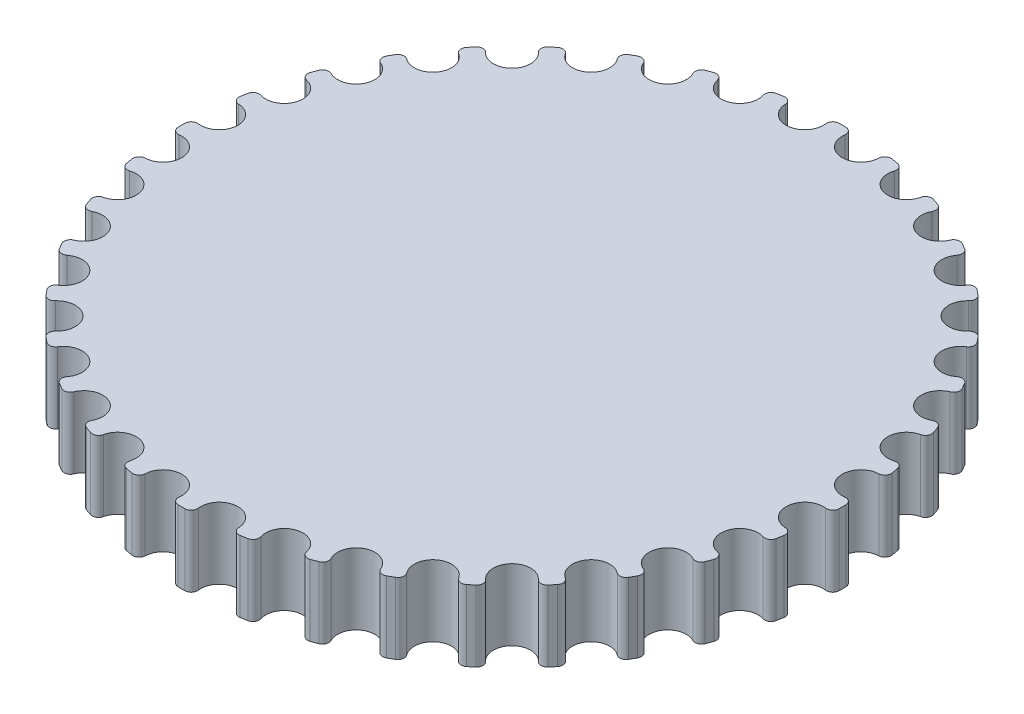
SolidWorks part; units mm, degrees
ref_plane "Front Plane" through (0, 0, 0) normal (0, 0, 1) x (1, 0, 0)
ref_plane "Top Plane" through (0, 0, 0) normal (0, 1, 0) x (1, 0, 0)
ref_plane "Right Plane" through (0, 0, 0) normal (1, 0, 0) x (0, 0, -1)
sketch "Sketch1" plane through (0, 0, 0) normal (0, 1, 0) x (1, 0, 0)
  line L0 (0, 0) -> (27.8866, 0) construction
  line L1 (0, 0) -> (27.7805, 2.4305) construction
  circle A0 centre (0, 0) radius 27.8866 construction
  arc A1 (27.0068, 3.9419) -> (27.281, 0.8076) centre (27.072, 2.3685) ccw
  arc A2 (27.281, 0.8076) -> (27.8852, 0.2844) centre (27.3518, 0.2789) cw
  arc A3 (27.8852, 0.2844) -> (27.8866, 0) centre (0, 0) cw
  arc A4 (27.0068, 3.9419) -> (27.5109, 4.5621) centre (26.9847, 4.4749) ccw
  arc A5 (27.5109, 4.5621) -> (27.463, 4.8425) centre (0, 0) ccw
  arc A6 (27.5109, -4.5621) -> (27.463, -4.8425) centre (0, 0) cw
  arc A7 (27.0068, -3.9419) -> (27.5109, -4.5621) centre (26.9847, -4.4749) cw
  arc A8 (27.281, -0.8076) -> (27.0068, -3.9419) centre (27.072, -2.3685) ccw
  arc A9 (27.281, -0.8076) -> (27.8852, -0.2844) centre (27.3518, -0.2789) ccw
  arc A10 (27.8852, -0.2844) -> (27.8866, 0) centre (0, 0) ccw
  arc A11 (26.3008, -9.2701) -> (26.2049, -9.5378) centre (0, 0) cw
  arc A12 (25.912, -8.5717) -> (26.3008, -9.2701) centre (25.7977, -9.0928) cw
  arc A13 (26.7263, -5.5327) -> (25.912, -8.5717) centre (26.2495, -7.0335) ccw
  arc A14 (26.7263, -5.5327) -> (27.4122, -5.1223) centre (26.8878, -5.0243) ccw
  arc A15 (27.4122, -5.1223) -> (27.463, -4.8425) centre (0, 0) ccw
  arc A16 (24.2915, -13.6963) -> (24.1505, -13.9433) centre (0, 0) cw
  arc A17 (24.0299, -12.9411) -> (24.2915, -13.6963) centre (23.8268, -13.4343) cw
  arc A18 (25.3596, -10.0896) -> (24.0299, -12.9411) centre (24.6293, -11.4848) ccw
  arc A19 (25.3596, -10.0896) -> (26.1062, -9.8045) centre (25.6069, -9.617) ccw
  arc A20 (26.1062, -9.8045) -> (26.2049, -9.5378) centre (0, 0) ccw
  arc A21 (21.5441, -17.7064) -> (21.3624, -17.9252) centre (0, 0) cw
  arc A22 (21.4176, -16.9172) -> (21.5441, -17.7064) centre (21.132, -17.3677) cw
  arc A23 (23.2222, -14.3399) -> (21.4176, -16.9172) centre (22.2608, -15.5872) ccw
  arc A24 (23.2222, -14.3399) -> (24.0071, -14.1889) centre (23.5479, -13.9175) ccw
  arc A25 (24.0071, -14.1889) -> (24.1505, -13.9433) centre (0, 0) ccw
  arc A26 (18.1421, -21.1785) -> (17.9252, -21.3624) centre (0, 0) cw
  arc A27 (18.1546, -20.3793) -> (18.1421, -21.1785) centre (17.7951, -20.7734) cw
  arc A28 (20.3793, -18.1546) -> (18.1546, -20.3793) centre (19.2159, -19.2159) ccw
  arc A29 (20.3793, -18.1546) -> (21.1785, -18.1421) centre (20.7734, -17.7951) ccw
  arc A30 (21.1785, -18.1421) -> (21.3624, -17.9252) centre (0, 0) ccw
  arc A31 (14.1889, -24.0071) -> (13.9433, -24.1505) centre (0, 0) cw
  arc A32 (14.3399, -23.2222) -> (14.1889, -24.0071) centre (13.9175, -23.5479) cw
  arc A33 (16.9172, -21.4176) -> (14.3399, -23.2222) centre (15.5872, -22.2608) ccw
  arc A34 (16.9172, -21.4176) -> (17.7064, -21.5441) centre (17.3677, -21.132) ccw
  arc A35 (17.7064, -21.5441) -> (17.9252, -21.3624) centre (0, 0) ccw
  arc A36 (9.8045, -26.1062) -> (9.5378, -26.2049) centre (0, 0) cw
  arc A37 (10.0896, -25.3596) -> (9.8045, -26.1062) centre (9.617, -25.6069) cw
  arc A38 (12.9411, -24.0299) -> (10.0896, -25.3596) centre (11.4848, -24.6293) ccw
  arc A39 (12.9411, -24.0299) -> (13.6963, -24.2915) centre (13.4343, -23.8268) ccw
  arc A40 (13.6963, -24.2915) -> (13.9433, -24.1505) centre (0, 0) ccw
  arc A41 (5.1223, -27.4122) -> (4.8425, -27.463) centre (0, 0) cw
  arc A42 (5.5327, -26.7263) -> (5.1223, -27.4122) centre (5.0243, -26.8878) cw
  arc A43 (8.5717, -25.912) -> (5.5327, -26.7263) centre (7.0335, -26.2495) ccw
  arc A44 (8.5717, -25.912) -> (9.2701, -26.3008) centre (9.0928, -25.7977) ccw
  arc A45 (9.2701, -26.3008) -> (9.5378, -26.2049) centre (0, 0) ccw
  arc A46 (0.2844, -27.8852) -> (0, -27.8866) centre (0, 0) cw
  arc A47 (0.8076, -27.281) -> (0.2844, -27.8852) centre (0.2789, -27.3518) cw
  arc A48 (3.9419, -27.0068) -> (0.8076, -27.281) centre (2.3685, -27.072) ccw
  arc A49 (3.9419, -27.0068) -> (4.5621, -27.5109) centre (4.4749, -26.9847) ccw
  arc A50 (4.5621, -27.5109) -> (4.8425, -27.463) centre (0, 0) ccw
  arc A51 (-4.5621, -27.5109) -> (-4.8425, -27.463) centre (0, 0) cw
  arc A52 (-3.9419, -27.0068) -> (-4.5621, -27.5109) centre (-4.4749, -26.9847) cw
  arc A53 (-0.8076, -27.281) -> (-3.9419, -27.0068) centre (-2.3685, -27.072) ccw
  arc A54 (-0.8076, -27.281) -> (-0.2844, -27.8852) centre (-0.2789, -27.3518) ccw
  arc A55 (-0.2844, -27.8852) -> (0, -27.8866) centre (0, 0) ccw
  arc A56 (-9.2701, -26.3008) -> (-9.5378, -26.2049) centre (0, 0) cw
  arc A57 (-8.5717, -25.912) -> (-9.2701, -26.3008) centre (-9.0928, -25.7977) cw
  arc A58 (-5.5327, -26.7263) -> (-8.5717, -25.912) centre (-7.0335, -26.2495) ccw
  arc A59 (-5.5327, -26.7263) -> (-5.1223, -27.4122) centre (-5.0243, -26.8878) ccw
  arc A60 (-5.1223, -27.4122) -> (-4.8425, -27.463) centre (0, 0) ccw
  arc A61 (-13.6963, -24.2915) -> (-13.9433, -24.1505) centre (0, 0) cw
  arc A62 (-12.9411, -24.0299) -> (-13.6963, -24.2915) centre (-13.4343, -23.8268) cw
  arc A63 (-10.0896, -25.3596) -> (-12.9411, -24.0299) centre (-11.4848, -24.6293) ccw
  arc A64 (-10.0896, -25.3596) -> (-9.8045, -26.1062) centre (-9.617, -25.6069) ccw
  arc A65 (-9.8045, -26.1062) -> (-9.5378, -26.2049) centre (0, 0) ccw
  arc A66 (-17.7064, -21.5441) -> (-17.9252, -21.3624) centre (0, 0) cw
  arc A67 (-16.9172, -21.4176) -> (-17.7064, -21.5441) centre (-17.3677, -21.132) cw
  arc A68 (-14.3399, -23.2222) -> (-16.9172, -21.4176) centre (-15.5872, -22.2608) ccw
  arc A69 (-14.3399, -23.2222) -> (-14.1889, -24.0071) centre (-13.9175, -23.5479) ccw
  arc A70 (-14.1889, -24.0071) -> (-13.9433, -24.1505) centre (0, 0) ccw
  arc A71 (-21.1785, -18.1421) -> (-21.3624, -17.9252) centre (0, 0) cw
  arc A72 (-20.3793, -18.1546) -> (-21.1785, -18.1421) centre (-20.7734, -17.7951) cw
  arc A73 (-18.1546, -20.3793) -> (-20.3793, -18.1546) centre (-19.2159, -19.2159) ccw
  arc A74 (-18.1546, -20.3793) -> (-18.1421, -21.1785) centre (-17.7951, -20.7734) ccw
  arc A75 (-18.1421, -21.1785) -> (-17.9252, -21.3624) centre (0, 0) ccw
  arc A76 (-24.0071, -14.1889) -> (-24.1505, -13.9433) centre (0, 0) cw
  arc A77 (-23.2222, -14.3399) -> (-24.0071, -14.1889) centre (-23.5479, -13.9175) cw
  arc A78 (-21.4176, -16.9172) -> (-23.2222, -14.3399) centre (-22.2608, -15.5872) ccw
  arc A79 (-21.4176, -16.9172) -> (-21.5441, -17.7064) centre (-21.132, -17.3677) ccw
  arc A80 (-21.5441, -17.7064) -> (-21.3624, -17.9252) centre (0, 0) ccw
  arc A81 (-26.1062, -9.8045) -> (-26.2049, -9.5378) centre (0, 0) cw
  arc A82 (-25.3596, -10.0896) -> (-26.1062, -9.8045) centre (-25.6069, -9.617) cw
  arc A83 (-24.0299, -12.9411) -> (-25.3596, -10.0896) centre (-24.6293, -11.4848) ccw
  arc A84 (-24.0299, -12.9411) -> (-24.2915, -13.6963) centre (-23.8268, -13.4343) ccw
  arc A85 (-24.2915, -13.6963) -> (-24.1505, -13.9433) centre (0, 0) ccw
  arc A86 (-27.4122, -5.1223) -> (-27.463, -4.8425) centre (0, 0) cw
  arc A87 (-26.7263, -5.5327) -> (-27.4122, -5.1223) centre (-26.8878, -5.0243) cw
  arc A88 (-25.912, -8.5717) -> (-26.7263, -5.5327) centre (-26.2495, -7.0335) ccw
  arc A89 (-25.912, -8.5717) -> (-26.3008, -9.2701) centre (-25.7977, -9.0928) ccw
  arc A90 (-26.3008, -9.2701) -> (-26.2049, -9.5378) centre (0, 0) ccw
  arc A91 (-27.8852, -0.2844) -> (-27.8866, 0) centre (0, 0) cw
  arc A92 (-27.281, -0.8076) -> (-27.8852, -0.2844) centre (-27.3518, -0.2789) cw
  arc A93 (-27.0068, -3.9419) -> (-27.281, -0.8076) centre (-27.072, -2.3685) ccw
  arc A94 (-27.0068, -3.9419) -> (-27.5109, -4.5621) centre (-26.9847, -4.4749) ccw
  arc A95 (-27.5109, -4.5621) -> (-27.463, -4.8425) centre (0, 0) ccw
  arc A96 (-27.5109, 4.5621) -> (-27.463, 4.8425) centre (0, 0) cw
  arc A97 (-27.0068, 3.9419) -> (-27.5109, 4.5621) centre (-26.9847, 4.4749) cw
  arc A98 (-27.281, 0.8076) -> (-27.0068, 3.9419) centre (-27.072, 2.3685) ccw
  arc A99 (-27.281, 0.8076) -> (-27.8852, 0.2844) centre (-27.3518, 0.2789) ccw
  arc A100 (-27.8852, 0.2844) -> (-27.8866, 0) centre (0, 0) ccw
  arc A101 (-26.3008, 9.2701) -> (-26.2049, 9.5378) centre (0, 0) cw
  arc A102 (-25.912, 8.5717) -> (-26.3008, 9.2701) centre (-25.7977, 9.0928) cw
  arc A103 (-26.7263, 5.5327) -> (-25.912, 8.5717) centre (-26.2495, 7.0335) ccw
  arc A104 (-26.7263, 5.5327) -> (-27.4122, 5.1223) centre (-26.8878, 5.0243) ccw
  arc A105 (-27.4122, 5.1223) -> (-27.463, 4.8425) centre (0, 0) ccw
  arc A106 (-24.2915, 13.6963) -> (-24.1505, 13.9433) centre (0, 0) cw
  arc A107 (-24.0299, 12.9411) -> (-24.2915, 13.6963) centre (-23.8268, 13.4343) cw
  arc A108 (-25.3596, 10.0896) -> (-24.0299, 12.9411) centre (-24.6293, 11.4848) ccw
  arc A109 (-25.3596, 10.0896) -> (-26.1062, 9.8045) centre (-25.6069, 9.617) ccw
  arc A110 (-26.1062, 9.8045) -> (-26.2049, 9.5378) centre (0, 0) ccw
  arc A111 (-21.5441, 17.7064) -> (-21.3624, 17.9252) centre (0, 0) cw
  arc A112 (-21.4176, 16.9172) -> (-21.5441, 17.7064) centre (-21.132, 17.3677) cw
  arc A113 (-23.2222, 14.3399) -> (-21.4176, 16.9172) centre (-22.2608, 15.5872) ccw
  arc A114 (-23.2222, 14.3399) -> (-24.0071, 14.1889) centre (-23.5479, 13.9175) ccw
  arc A115 (-24.0071, 14.1889) -> (-24.1505, 13.9433) centre (0, 0) ccw
  arc A116 (-18.1421, 21.1785) -> (-17.9252, 21.3624) centre (0, 0) cw
  arc A117 (-18.1546, 20.3793) -> (-18.1421, 21.1785) centre (-17.7951, 20.7734) cw
  arc A118 (-20.3793, 18.1546) -> (-18.1546, 20.3793) centre (-19.2159, 19.2159) ccw
  arc A119 (-20.3793, 18.1546) -> (-21.1785, 18.1421) centre (-20.7734, 17.7951) ccw
  arc A120 (-21.1785, 18.1421) -> (-21.3624, 17.9252) centre (0, 0) ccw
  arc A121 (-14.1889, 24.0071) -> (-13.9433, 24.1505) centre (0, 0) cw
  arc A122 (-14.3399, 23.2222) -> (-14.1889, 24.0071) centre (-13.9175, 23.5479) cw
  arc A123 (-16.9172, 21.4176) -> (-14.3399, 23.2222) centre (-15.5872, 22.2608) ccw
  arc A124 (-16.9172, 21.4176) -> (-17.7064, 21.5441) centre (-17.3677, 21.132) ccw
  arc A125 (-17.7064, 21.5441) -> (-17.9252, 21.3624) centre (0, 0) ccw
  arc A126 (-9.8045, 26.1062) -> (-9.5378, 26.2049) centre (0, 0) cw
  arc A127 (-10.0896, 25.3596) -> (-9.8045, 26.1062) centre (-9.617, 25.6069) cw
  arc A128 (-12.9411, 24.0299) -> (-10.0896, 25.3596) centre (-11.4848, 24.6293) ccw
  arc A129 (-12.9411, 24.0299) -> (-13.6963, 24.2915) centre (-13.4343, 23.8268) ccw
  arc A130 (-13.6963, 24.2915) -> (-13.9433, 24.1505) centre (0, 0) ccw
  arc A131 (-5.1223, 27.4122) -> (-4.8425, 27.463) centre (0, 0) cw
  arc A132 (-5.5327, 26.7263) -> (-5.1223, 27.4122) centre (-5.0243, 26.8878) cw
  arc A133 (-8.5717, 25.912) -> (-5.5327, 26.7263) centre (-7.0335, 26.2495) ccw
  arc A134 (-8.5717, 25.912) -> (-9.2701, 26.3008) centre (-9.0928, 25.7977) ccw
  arc A135 (-9.2701, 26.3008) -> (-9.5378, 26.2049) centre (0, 0) ccw
  arc A136 (-0.2844, 27.8852) -> (0, 27.8866) centre (0, 0) cw
  arc A137 (-0.8076, 27.281) -> (-0.2844, 27.8852) centre (-0.2789, 27.3518) cw
  arc A138 (-3.9419, 27.0068) -> (-0.8076, 27.281) centre (-2.3685, 27.072) ccw
  arc A139 (-3.9419, 27.0068) -> (-4.5621, 27.5109) centre (-4.4749, 26.9847) ccw
  arc A140 (-4.5621, 27.5109) -> (-4.8425, 27.463) centre (0, 0) ccw
  arc A141 (4.5621, 27.5109) -> (4.8425, 27.463) centre (0, 0) cw
  arc A142 (3.9419, 27.0068) -> (4.5621, 27.5109) centre (4.4749, 26.9847) cw
  arc A143 (0.8076, 27.281) -> (3.9419, 27.0068) centre (2.3685, 27.072) ccw
  arc A144 (0.8076, 27.281) -> (0.2844, 27.8852) centre (0.2789, 27.3518) ccw
  arc A145 (0.2844, 27.8852) -> (0, 27.8866) centre (0, 0) ccw
  arc A146 (9.2701, 26.3008) -> (9.5378, 26.2049) centre (0, 0) cw
  arc A147 (8.5717, 25.912) -> (9.2701, 26.3008) centre (9.0928, 25.7977) cw
  arc A148 (5.5327, 26.7263) -> (8.5717, 25.912) centre (7.0335, 26.2495) ccw
  arc A149 (5.5327, 26.7263) -> (5.1223, 27.4122) centre (5.0243, 26.8878) ccw
  arc A150 (5.1223, 27.4122) -> (4.8425, 27.463) centre (0, 0) ccw
  arc A151 (13.6963, 24.2915) -> (13.9433, 24.1505) centre (0, 0) cw
  arc A152 (12.9411, 24.0299) -> (13.6963, 24.2915) centre (13.4343, 23.8268) cw
  arc A153 (10.0896, 25.3596) -> (12.9411, 24.0299) centre (11.4848, 24.6293) ccw
  arc A154 (10.0896, 25.3596) -> (9.8045, 26.1062) centre (9.617, 25.6069) ccw
  arc A155 (9.8045, 26.1062) -> (9.5378, 26.2049) centre (0, 0) ccw
  arc A156 (17.7064, 21.5441) -> (17.9252, 21.3624) centre (0, 0) cw
  arc A157 (16.9172, 21.4176) -> (17.7064, 21.5441) centre (17.3677, 21.132) cw
  arc A158 (14.3399, 23.2222) -> (16.9172, 21.4176) centre (15.5872, 22.2608) ccw
  arc A159 (14.3399, 23.2222) -> (14.1889, 24.0071) centre (13.9175, 23.5479) ccw
  arc A160 (14.1889, 24.0071) -> (13.9433, 24.1505) centre (0, 0) ccw
  arc A161 (21.1785, 18.1421) -> (21.3624, 17.9252) centre (0, 0) cw
  arc A162 (20.3793, 18.1546) -> (21.1785, 18.1421) centre (20.7734, 17.7951) cw
  arc A163 (18.1546, 20.3793) -> (20.3793, 18.1546) centre (19.2159, 19.2159) ccw
  arc A164 (18.1546, 20.3793) -> (18.1421, 21.1785) centre (17.7951, 20.7734) ccw
  arc A165 (18.1421, 21.1785) -> (17.9252, 21.3624) centre (0, 0) ccw
  arc A166 (24.0071, 14.1889) -> (24.1505, 13.9433) centre (0, 0) cw
  arc A167 (23.2222, 14.3399) -> (24.0071, 14.1889) centre (23.5479, 13.9175) cw
  arc A168 (21.4176, 16.9172) -> (23.2222, 14.3399) centre (22.2608, 15.5872) ccw
  arc A169 (21.4176, 16.9172) -> (21.5441, 17.7064) centre (21.132, 17.3677) ccw
  arc A170 (21.5441, 17.7064) -> (21.3624, 17.9252) centre (0, 0) ccw
  arc A171 (26.1062, 9.8045) -> (26.2049, 9.5378) centre (0, 0) cw
  arc A172 (25.3596, 10.0896) -> (26.1062, 9.8045) centre (25.6069, 9.617) cw
  arc A173 (24.0299, 12.9411) -> (25.3596, 10.0896) centre (24.6293, 11.4848) ccw
  arc A174 (24.0299, 12.9411) -> (24.2915, 13.6963) centre (23.8268, 13.4343) ccw
  arc A175 (24.2915, 13.6963) -> (24.1505, 13.9433) centre (0, 0) ccw
  arc A176 (27.4122, 5.1223) -> (27.463, 4.8425) centre (0, 0) cw
  arc A177 (26.7263, 5.5327) -> (27.4122, 5.1223) centre (26.8878, 5.0243) cw
  arc A178 (25.912, 8.5717) -> (26.7263, 5.5327) centre (26.2495, 7.0335) ccw
  arc A179 (25.912, 8.5717) -> (26.3008, 9.2701) centre (25.7977, 9.0928) ccw
  arc A180 (26.3008, 9.2701) -> (26.2049, 9.5378) centre (0, 0) ccw
  point P23 (25.5032, 2.2312)
  point P44 (0, 0)
  dimension "D1" = 55.7733
  dimension "D3" = 1.5748
  dimension "D4" = 0.5334
  dimension "D2" = 5
  dimension "D5" = 2.286
  dimension "D6" = 36
extrude "Boss-Extrude1" add sketch "Sketch1" along normal blind 6 contours A79 A80 A71 A72 A73 A74 A75 A66 A67 A68 A69 A70 A61 A62 A63 A64 A65 A56 A57 A58 A59 A60 A51 A52 A53 A54 A55 A46 A47 A48 A49 A50 A41 A42 A43 A44 A45 A36 A37 A38 A39 A40 A31 A32 A33 A34 A35 A26 A27 A28 A29
sketch "BeltOuterFace" plane through (0, 0, 0) normal (0, 1, 0) x (1, 0, 0)
  circle A0 centre (0, 0) radius 29.464 construction
  dimension "D1" = 58.928
equation "\"T\"= 36"
equation "\"P\"= 5mm"
equation "\"TanD\" = \"PD\" - \"BeltWidth\" * \"BeltWidthTune\""
equation "\"Angle\"= 360 / \"T\""
equation "\"D1@Sketch1\"=\"TanD\""
equation "\"D2@Sketch1\"=\"Angle\"/2"
equation "\"D6@Sketch1\"=\"T\""
equation "\"W\"= 6mm"
equation "\"D1@Boss-Extrude1\"=\"W\""
equation "\"TolRatio\"= 32 / 33"
equation "\"PD\"= \"T\" * \"P\" / PI"
equation "\"BeltWidth\"= 1.74mm"
equation "\"BeltWidthTune\" = .875"
